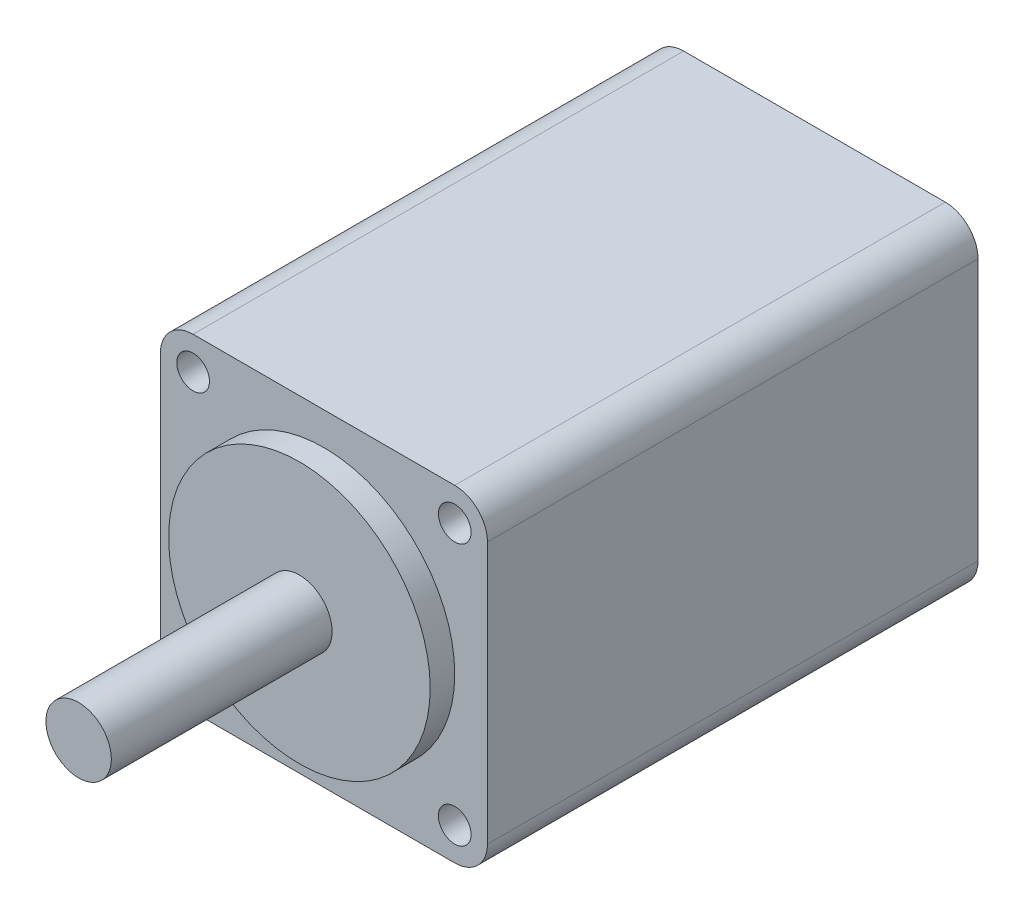
SolidWorks part; units mm, degrees
ref_plane "Front Plane" through (0, 0, 0) normal (0, 0, 1) x (1, 0, 0)
ref_plane "Top Plane" through (0, 0, 0) normal (0, 1, 0) x (1, 0, 0)
ref_plane "Right Plane" through (0, 0, 0) normal (1, 0, 0) x (0, 0, -1)
sketch "Sketch1" plane through (0, 0, 0) normal (0, 0, 1) x (1, 0, 0)
  line L1 (-10, 10) -> (10, 10)
  line L2 (-10, 10) -> (-10, -10)
  line L3 (-10, -10) -> (10, -10)
  line L4 (10, 10) -> (10, -10)
  line L5 (-10, 10) -> (10, -10) construction
  line L6 (-10, -10) -> (10, 10) construction
  point P0 (0, 0)
  dimension "D1" = 20
extrude "Boss-Extrude1" add sketch "Sketch1" against normal blind 30
sketch "Sketch2" plane through (0, 0, 0) normal (0, 0, 1) x (1, 0, 0)
  line L1 (-8, 8) -> (8, 8) construction
  line L2 (-8, 8) -> (-8, -8) construction
  line L3 (-8, -8) -> (8, -8) construction
  line L4 (8, 8) -> (8, -8) construction
  line L5 (-8, 8) -> (8, -8) construction
  line L6 (-8, -8) -> (8, 8) construction
  circle A0 centre (-8, 8) radius 1
  circle A1 centre (8, 8) radius 1
  circle A2 centre (8, -8) radius 1
  circle A3 centre (-8, -8) radius 1
  point P0 (0, 0)
  dimension "D2" = 2
  dimension "D1" = 16
extrude "Cut-Extrude1" cut sketch "Sketch2" against normal blind 6
fillet "Fillet1" radius 2 4 edges at (-10, -10, -15) (-10, 10, -15) (10, -10, -15) (10, 10, -15)
sketch "Sketch3" plane through (0, 0, 0) normal (0, 0, 1) x (1, 0, 0)
  circle A0 centre (0, 0) radius 8
  dimension "D1" = 16
extrude "Boss-Extrude2" add sketch "Sketch3" along normal blind 1.5
sketch "Sketch4" plane through (0, 0, 1.5) normal (0, 0, 1) x (1, 0, 0)
  circle A0 centre (0, 0) radius 2
  dimension "D1" = 4
extrude "Boss-Extrude3" add sketch "Sketch4" along normal offset from surface (13.5 mm away) 15 up to face at (8, 0, 0) offset beyond the face yes
